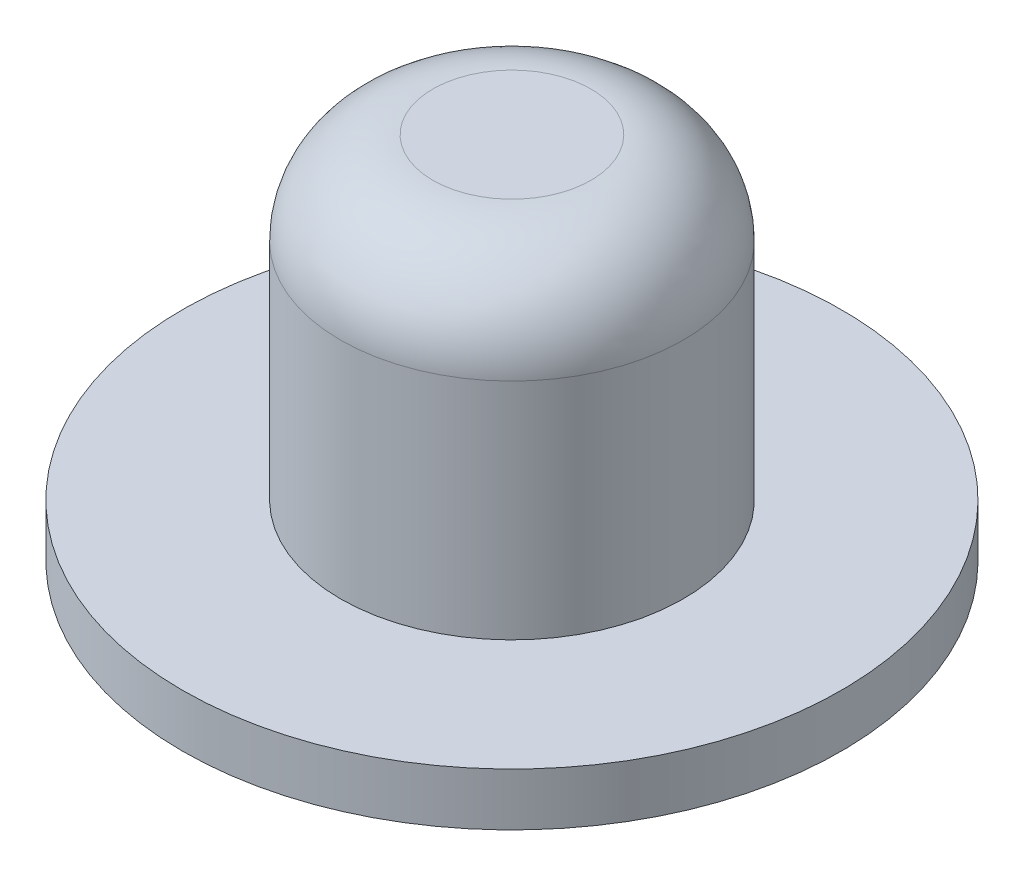
SolidWorks part; units mm, degrees
ref_plane "Plan de face" through (0, 0, 0) normal (0, 0, 1) x (1, 0, 0)
ref_plane "Plan de dessus" through (0, 0, 0) normal (0, 1, 0) x (1, 0, 0)
ref_plane "Plan de droite" through (0, 0, 0) normal (1, 0, 0) x (0, 0, -1)
sketch "Esquisse1" plane through (0, 0, 0) normal (0, 1, 0) x (1, 0, 0)
  circle A0 centre (0, 0) radius 12.5
  dimension "D1" = 25
extrude "Boss.-Extru.1" add sketch "Esquisse1" along normal blind 2
sketch "Esquisse2" plane through (0, 2, 0) normal (0, 1, 0) x (1, 0, 0)
  circle A0 centre (0, 0) radius 6.5
  dimension "D1" = 13
extrude "Boss.-Extru.2" add sketch "Esquisse2" along normal blind 12
fillet "Congé1" radius 3.5 1 edges at (0, 14, 6.5)
